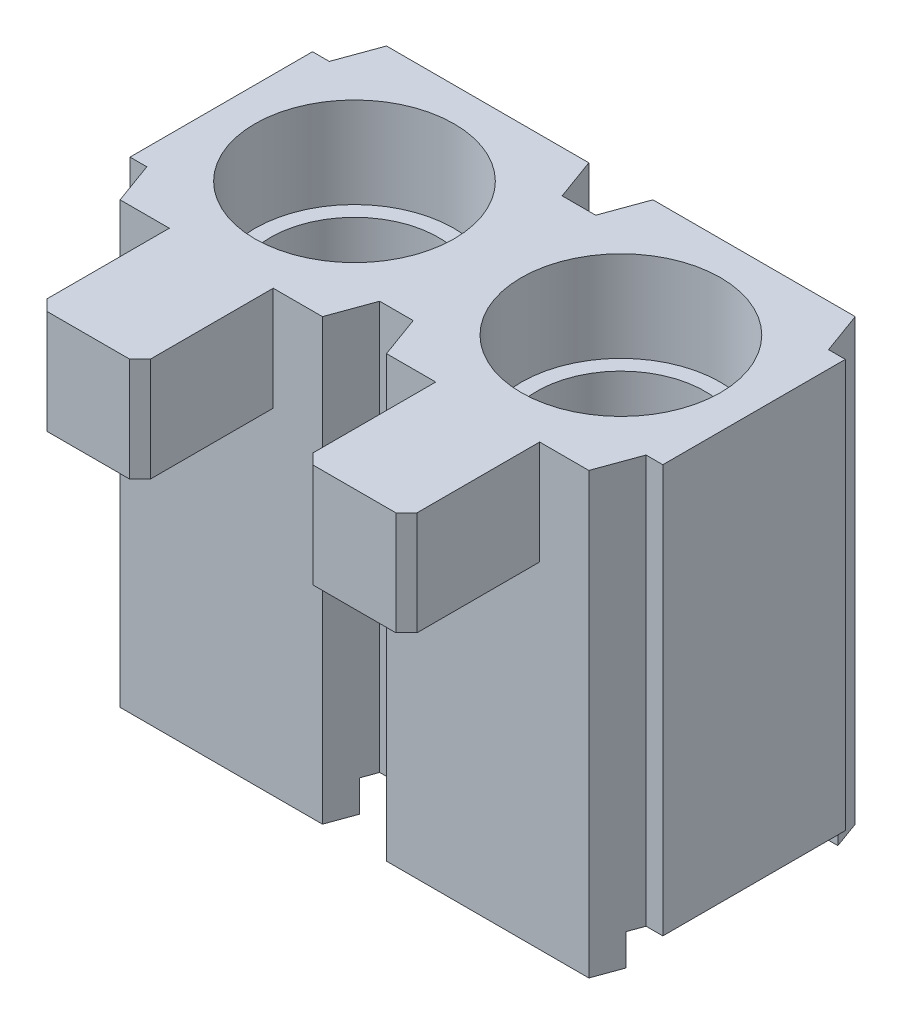
SolidWorks part; units mm, degrees
material "PCT Polyester"
ref_plane "Front Plane" through (0, 0, 0) normal (0, 0, 1) x (1, 0, 0)
ref_plane "Top Plane" through (0, 0, 0) normal (0, 1, 0) x (1, 0, 0)
ref_plane "Right Plane" through (0, 0, 0) normal (1, 0, 0) x (0, 0, -1)
sketch "Sketch1" plane through (0, 0, 0) normal (0, 1, 0) x (1, 0, 0)
  line L0 (4.7744, 0.4) -> (4.6144, 0.4)
  line L1 (4.7744, 2.1399) -> (4.7744, 0.4)
  line L2 (-0.3056, 2.1399) -> (-0.1456, 2.1399)
  line L3 (-0.3056, 2.1399) -> (-0.3056, 0.4)
  line L4 (0, 0) -> (4.4687, 0)
  line L5 (0, 2.54) -> (-0.1456, 2.1399)
  line L6 (0, 0) -> (-0.1456, 0.4)
  line L7 (-0.3056, 0.4) -> (-0.1456, 0.4)
  line L9 (4.4687, 0) -> (4.6144, 0.4)
  line L10 (4.4687, 2.54) -> (4.6144, 2.1399)
  line L11 (4.7744, 2.1399) -> (4.6144, 2.1399)
  line L16 (4.4687, 2.54) -> (0, 2.54)
  dimension "D2" = 2.54
  dimension "D3" = 20
  dimension "D4" = 0.4
  dimension "D5" = 0.4
  dimension "D7" = 0.16
  dimension "INSLENGTH" = 5.08
extrude "Extrude1" add sketch "Sketch1" against normal blind 4.191
hole_wizard "Hole1" positions "3DSketch1" profile "Sketch2" legacy end condition through all
sketch3d "3DSketch1"
  line L2 (-0.3056, 0, -2.1399) -> (-0.3056, 0, -0.4) construction
  line L3 (4.4687, 0, -2.54) -> (0, 0, -2.54) construction
  point P0 (0.9644, 0, -1.27)
  dimension "D1" = 1.27
  dimension "D2" = 1.27
sketch "Sketch2" plane through (0.9644, 0, -1.27) normal (1, 0, 0) x (0, 0, 1)
  line L0 (0, 0) -> (0, 4.191)
  line L1 (0, 4.191) -> (0.8014, 4.191)
  line L2 (0.8014, 4.191) -> (0.8014, 0.8636)
  line L3 (0.8014, 0.8636) -> (0.95, 0.8636)
  line L4 (0.95, 0.8636) -> (0.95, 0)
  line L5 (0.95, 0) -> (0, 0)
  line L6 (0, 110) -> (0, -10) construction
  dimension "Diameter" = 1.6027
  dimension "Depth" = 4.191
  dimension "C-Bore Diameter" = 1.8999
  dimension "C-Bore Depth" = 0.8636
sketch "Sketch3" plane through (0, 0, 0) normal (0, 1, 0) x (1, 0, 0)
  line L0 (1.9288, 0) -> (2.54, 0)
  line L2 (0, 0) -> (4.4687, 0) construction
  line L5 (2.0744, 0.4) -> (1.9288, 0)
  line L6 (2.3944, 0.4) -> (2.54, 0)
  line L7 (4.4687, 2.54) -> (0, 2.54) construction
  line L8 (2.0744, 0.4) -> (2.3944, 0.4)
  line L10 (2.0744, 2.1399) -> (2.3944, 2.1399)
  line L11 (2.3944, 2.1399) -> (2.54, 2.54)
  line L12 (2.0744, 2.1399) -> (1.9288, 2.54)
  line L13 (1.9288, 2.54) -> (2.54, 2.54)
  line L17 (-0.3056, 2.1399) -> (-0.3056, 0.4) construction
  dimension "D1" = 0.4
  dimension "D2" = 0.32
  dimension "D3" = 70
  dimension "D4" = 0.6112
  dimension "D5" = 0.4001
  dimension "D6" = 2.2344
extrude "Extrude2" cut sketch "Sketch3" against normal blind 7.0104
pattern_linear "LPattern1" count 2 spacing 2.54 along (1, 0, 0) of "Hole1"
pattern_linear "LPattern2" count 35 spacing 2.54 along (1, 0, 0) of "Extrude2"
sketch "Sketch4" plane through (4.7744, 0, 0) normal (1, 0, 0) x (0, 0, -1)
  line L0 (0, -4.191) -> (0, 0) construction
  line L1 (0, -4.191) -> (0.4, -4.191) construction
  line L2 (2.2799, -4.191) -> (2.2799, -3.891)
  line L3 (0.2601, -4.191) -> (0.2601, -3.891)
  line L4 (2.1399, -4.191) -> (2.54, -4.191) construction
  line L6 (2.54, -4.191) -> (2.54, 0) construction
  line L7 (2.2799, -3.891) -> (0.2601, -3.891)
  line L9 (2.2799, -4.191) -> (0.2601, -4.191)
  dimension "D1" = 0.2601
  dimension "D2" = 0.3
  dimension "D3" = 0.2601
extrude "Extrude3" cut sketch "Sketch4" against normal through all
sketch "Sketch5" plane through (0, 0, 0) normal (0, 1, 0) x (-1, 0, 0)
  line L1 (-0.4691, 1.1684) -> (-0.5707, 1.27)
  line L4 (-0.4691, 0) -> (-1.4597, 0)
  line L9 (-1.4597, 1.1684) -> (-1.3581, 1.27)
  line L10 (-0.5707, 1.27) -> (-1.3581, 1.27)
  line L11 (-0.4691, 0) -> (-0.4691, 1.1684)
  line L12 (-1.4597, 0) -> (-1.4597, 1.1684)
  circle A1 centre (-0.9644, -1.27) radius 0.8014 construction
  dimension "D5" = 45
  dimension "D2" = 1.27
  dimension "D3" = 0.4953
  dimension "D1" = 1.27
  dimension "D4" = 0.9906
  dimension "D6" = 0.1016
  dimension "D7" = 45
extrude "Boss-Extrude1" add sketch "Sketch5" against normal blind 0.9906
pattern_linear "LPattern3" count 2 spacing 2.54 along (1, 0, 0) of "Boss-Extrude1"
